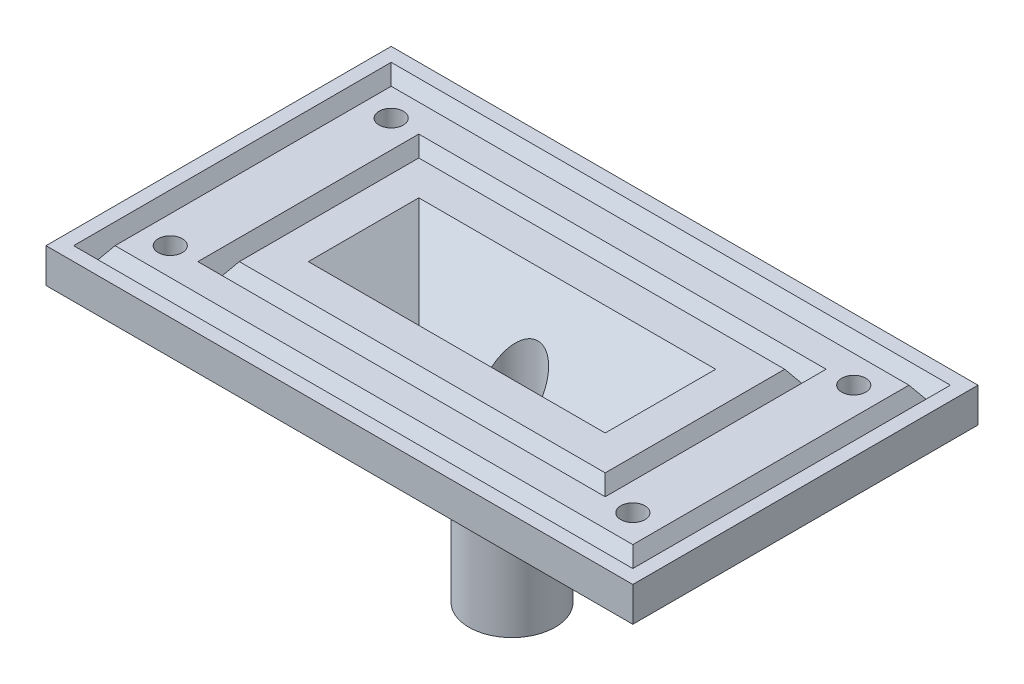
SolidWorks part; units mm, degrees
ref_plane "Front Plane" through (0, 0, 0) normal (0, 0, 1) x (1, 0, 0)
ref_plane "Top Plane" through (0, 0, 0) normal (0, 1, 0) x (1, 0, 0)
ref_plane "Right Plane" through (0, 0, 0) normal (1, 0, 0) x (0, 0, -1)
sketch "Sketch1" plane through (0, 0, 0) normal (0, 1, 0) x (1, 0, 0)
  line L1 (42.5, -25) -> (-42.5, -25)
  line L2 (42.5, -25) -> (42.5, 25)
  line L3 (42.5, 25) -> (-42.5, 25)
  line L4 (-42.5, -25) -> (-42.5, 25)
  line L5 (42.5, -25) -> (-42.5, 25) construction
  line L6 (42.5, 25) -> (-42.5, -25) construction
  point P0 (0, 0)
extrude "Base Plate" add sketch "Sketch1" along normal blind 5
sketch "Sketch4" plane through (0, 5, 0) normal (0, 1, 0) x (1, 0, 0)
  line L0 (-40.5, -23) -> (-40.5, 23)
  line L1 (-40.5, 23) -> (40.5, 23)
  line L2 (40.5, 23) -> (40.5, -23)
  line L3 (40.5, -23) -> (-40.5, -23)
  line L4 (-37.5, -20) -> (-37.5, 20)
  line L5 (-37.5, 20) -> (37.5, 20)
  line L6 (37.5, 20) -> (37.5, -20)
  line L7 (37.5, -20) -> (-37.5, -20)
  line L8 (42.5, -25) -> (42.5, 25) construction
  line L9 (-42.5, 25) -> (-42.5, -25) construction
  line L10 (-42.5, -25) -> (42.5, -25) construction
  line L11 (42.5, 25) -> (-42.5, 25) construction
  dimension "D1" = 2
  dimension "D2" = 3
  dimension "D3" = 2
  dimension "D4" = 3
  dimension "D5" = 2
  dimension "D6" = 3
  dimension "D7" = 3
  dimension "D8" = 2
extrude "Sealant Cut - Outer" cut sketch "Sketch4" against normal blind 5 draft 35
sketch "Sketch7" plane through (0, 5, 0) normal (0, 1, 0) x (1, 0, 0)
  line L0 (37.5, 20) -> (-37.5, 20) construction
  line L1 (-37.5, 20) -> (-37.5, -20) construction
  line L2 (0, 0) -> (-11.5051, 0) construction
  line L4 (0, 13.9859) -> (0, 0) construction
  circle A0 centre (-33.5, 16) radius 1.75
  circle A1 centre (-33.5, -16) radius 1.75
  circle A2 centre (33.5, -16) radius 1.75
  circle A3 centre (33.5, 16) radius 1.75
  dimension "D1" = 3.5
  dimension "D2" = 4
  dimension "D3" = 4
extrude "Scre Cut" cut sketch "Sketch7" against normal blind 5
sketch "Sketch8" plane through (0, 0, 0) normal (0, -1, 0) x (1, 0, 0)
  line L0 (0, 0) -> (0, -6.6439) construction
  line L2 (-4.9872, 0) -> (0, 0) construction
  circle A0 centre (-33.5, -16) radius 2.75
  circle A1 centre (-33.5, 16) radius 2.75
  circle A2 centre (33.5, 16) radius 2.75
  circle A3 centre (33.5, -16) radius 2.75
  dimension "D1" = 5.5
sketch "Sketch12" plane through (0, 5, 0) normal (0, 1, 0) x (1, 0, 0)
  line L0 (29.5, -16) -> (-29.5, -16)
  line L1 (-29.5, -16) -> (-29.5, 16)
  line L2 (-29.5, 16) -> (29.5, 16)
  line L3 (29.5, 16) -> (29.5, -16)
  line L4 (26.5, -13) -> (-26.5, -13)
  line L5 (-26.5, -13) -> (-26.5, 13)
  line L6 (-26.5, 13) -> (26.5, 13)
  line L7 (26.5, 13) -> (26.5, -13)
  line L8 (37.5, 20) -> (-37.5, 20) construction
  circle A0 centre (33.5, -16) radius 1.75 construction
  circle A3 centre (-33.5, 16) radius 1.75 construction
  circle A4 centre (33.5, 16) radius 1.75 construction
  dimension "D1" = 4
  dimension "D2" = 3
  dimension "D3" = 4
  dimension "D4" = 4
  dimension "D5" = 4
  dimension "D6" = 3
  dimension "D7" = 3
  dimension "D8" = 3
extrude "Sealant Cut - Inner" cut sketch "Sketch12" against normal blind 3 draft 35
sketch "Sketch13" plane through (0, 5, 0) normal (0, 1, 0) x (1, 0, 0)
  line L0 (26.5, -13) -> (26.5, 13) construction
  line L1 (-21.5, 8) -> (21.5, 8)
  line L2 (-21.5, 8) -> (-21.5, -8)
  line L3 (-21.5, -8) -> (21.5, -8)
  line L4 (21.5, 8) -> (21.5, -8)
  line L5 (-21.5, 8) -> (21.5, -8) construction
  line L6 (-21.5, -8) -> (21.5, 8) construction
  line L7 (-26.5, -13) -> (26.5, -13) construction
  point P0 (0, 0)
  dimension "D1" = 5
  dimension "D2" = 5
sketch "Sketch14" plane through (0, 0, 0) normal (0, -1, 0) x (1, 0, 0)
  line L1 (27.5, -13) -> (-27.5, -13)
  line L2 (27.5, -13) -> (27.5, 13)
  line L3 (27.5, 13) -> (-27.5, 13)
  line L4 (-27.5, -13) -> (-27.5, 13)
  line L5 (27.5, -13) -> (-27.5, 13) construction
  line L6 (27.5, 13) -> (-27.5, -13) construction
  point P0 (0, 0)
  dimension "D1" = 55
  dimension "D2" = 26
extrude "Base Block" add sketch "Sketch14" along normal blind 11
extrude "Drain" cut sketch "Sketch13" against normal blind 16 draft 40
sketch "Sketch15" plane through (0, -11, 0) normal (0, -1, 0) x (1, 0, 0)
  circle A0 centre (0, 0) radius 6.25
  dimension "D1" = 12.5
extrude "Hose connector" add sketch "Sketch15" along normal blind 20
sketch "Sketch16" plane through (0, -31, 0) normal (0, -1, 0) x (1, 0, 0)
  circle A0 centre (0, 0) radius 3.75
  circle A1 centre (0, 0) radius 6.25 construction
  dimension "D1" = 2.5
extrude "Drain Hole" cut sketch "Sketch16" against normal through all contours A0
fillet "Fillet1" radius 10 1 edges at (-27.5, -5.5, -13)
fillet "Fillet2" radius 10 1 edges at (27.5, -5.5, -13)
fillet "Fillet3" radius 10 1 edges at (27.5, -5.5, 13)
fillet "Fillet4" radius 10 1 edges at (-27.5, -5.5, 13)
extrude "Srew Heads" cut sketch "Sketch8" against normal blind 20 draft 45
